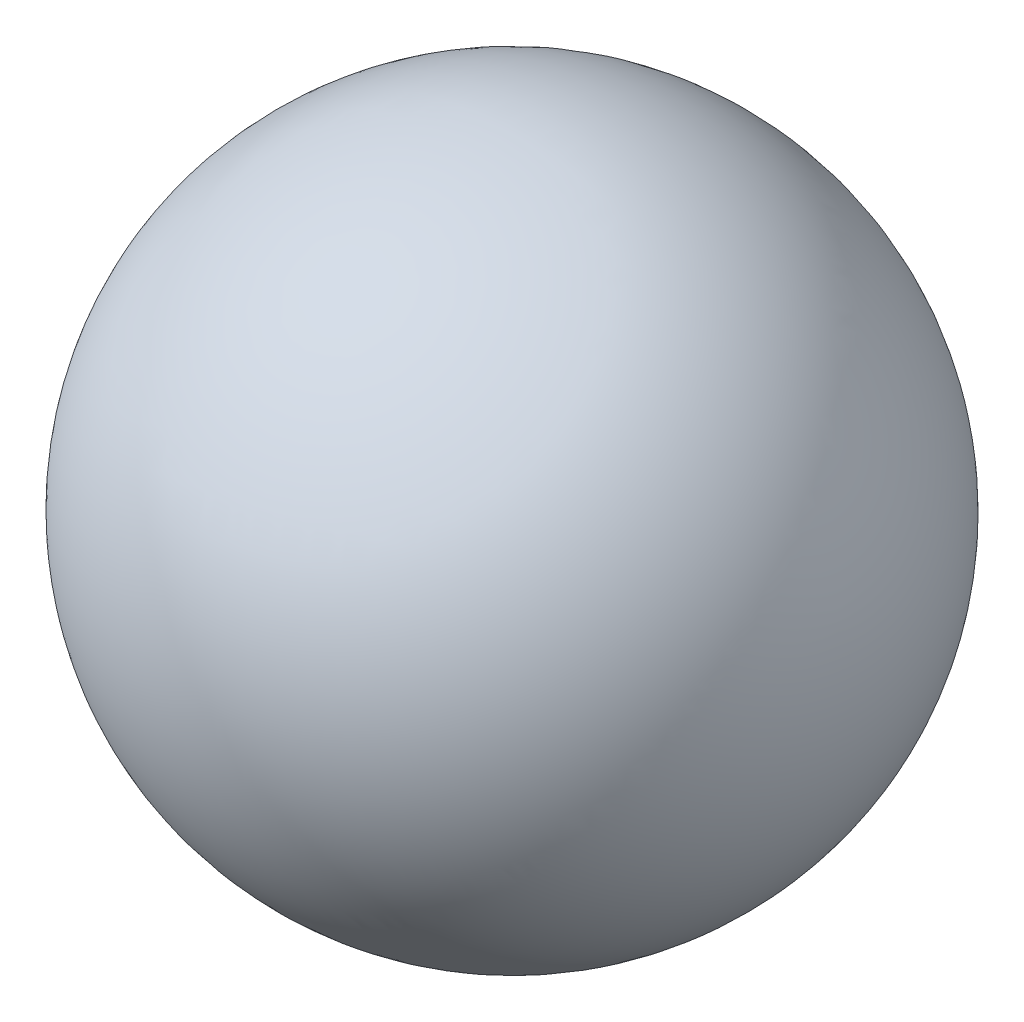
SolidWorks part; units mm, degrees
ref_plane "Front Plane" through (0, 0, 0) normal (0, 0, 1) x (1, 0, 0)
ref_plane "Top Plane" through (0, 0, 0) normal (0, 1, 0) x (1, 0, 0)
ref_plane "Right Plane" through (0, 0, 0) normal (1, 0, 0) x (0, 0, -1)
sketch "Sketch5" plane through (0, 0, 0) normal (0, 0, 1) x (1, 0, 0)
  line L0 (-197.1058, -19.1972) -> (-187.2538, -17.2268) construction
  line L1 (-197.0895, -19.1972) -> (-187.2669, -17.1906)
  arc A0 (-197.0895, -19.1972) -> (-187.2669, -17.1906) centre (-192.1665, -18.251) cw
revolve "Revolve1" add sketch "Sketch5" angle 360 about L1
